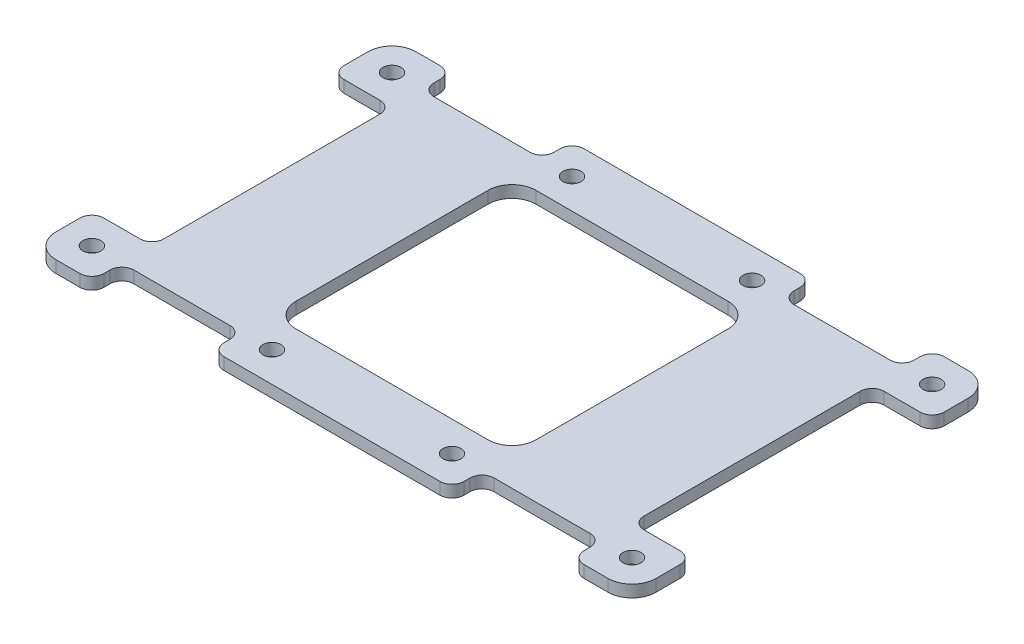
SolidWorks part; units mm, degrees
material "Thornel Mat VMA"
ref_plane "前视基准面" through (0, 0, 0) normal (0, 0, 1) x (1, 0, 0)
ref_plane "上视基准面" through (0, 0, 0) normal (0, 1, 0) x (1, 0, 0)
ref_plane "右视基准面" through (0, 0, 0) normal (1, 0, 0) x (0, 0, -1)
other "Configuration Table"
sketch "草图1" plane through (0, 0, 0) normal (0, 1, 0) x (1, 0, 0)
  line L1 (-50, -30) -> (50, -30)
  line L2 (-50, -30) -> (-50, 30)
  line L3 (-50, 30) -> (50, 30)
  line L4 (50, -30) -> (50, 30)
  line L5 (-50, -30) -> (50, 30) construction
  line L6 (-50, 30) -> (50, -30) construction
  point P0 (0, 0)
  dimension "D1" = 100
  dimension "D2" = 60
extrude "凸台-拉伸1" add sketch "草图1" along normal blind 2
sketch "草图3" plane through (0, 2, 0) normal (0, 1, 0) x (1, 0, 0)
  line L0 (-1000, 0) -> (49000, 0) construction
  line L1 (-42.4264, 42.4264) -> (0, 0) construction
  line L2 (-42.9749, 27.7358) -> (35312.3642, 35383.0749) construction
  line L3 (0, -1000) -> (0, 49000) construction
  circle A0 centre (0, 0) radius 60 construction
  circle A1 centre (-42.4264, 42.4264) radius 1.5
  circle A2 centre (-31.8198, 38.8909) radius 1.5
  circle A3 centre (-38.8909, 31.8198) radius 1.5
  circle A4 centre (-31.8198, -38.8909) radius 1.5
  circle A5 centre (-38.8909, -31.8198) radius 1.5
  circle A6 centre (-42.4264, -42.4264) radius 1.5
  circle A7 centre (31.8198, 38.8909) radius 1.5
  circle A8 centre (38.8909, 31.8198) radius 1.5
  circle A9 centre (42.4264, 42.4264) radius 1.5
  circle A10 centre (31.8198, -38.8909) radius 1.5
  circle A11 centre (42.4264, -42.4264) radius 1.5
  circle A12 centre (38.8909, -31.8198) radius 1.5
  dimension "D1" = 120
  dimension "D3" = 3
  dimension "D6" = 3
  dimension "D7" = 3
  dimension "D8" = 5
  dimension "D9" = 5
  dimension "D2" = 45
  dimension "D4" = 90
  dimension "D5" = 10
sketch "草图4" plane through (0, 2, 0) normal (0, 1, 0) x (1, 0, 0)
  line L1 (-20, -20) -> (20, -20)
  line L2 (-20, -20) -> (-20, 20)
  line L3 (-20, 20) -> (20, 20)
  line L4 (20, -20) -> (20, 20)
  line L5 (-20, -20) -> (20, 20) construction
  line L6 (-20, 20) -> (20, -20) construction
  point P0 (0, 0)
  dimension "D1" = 40
  dimension "D2" = 40
extrude "切除-拉伸3" cut sketch "草图4" against normal through all
sketch "草图5" plane through (0, 2, 0) normal (0, 1, 0) x (1, 0, 0)
  line L0 (-50, 30) -> (-50, -30) construction
  line L1 (-47, -20) -> (-45, -20)
  line L2 (-47, -20) -> (-47, 20)
  line L3 (-47, 20) -> (-45, 20)
  line L4 (-45, -20) -> (-45, 20)
  line L5 (-47, -20) -> (-45, 20) construction
  line L6 (-47, 20) -> (-45, -20) construction
  line L7 (0, -1000) -> (0, 49000) construction
  line L8 (47, -20) -> (45, -20)
  line L9 (47, 20) -> (45, 20)
  line L10 (45, -20) -> (45, 20)
  line L11 (47, -20) -> (47, 20)
  point P0 (-46, 0)
  dimension "D1" = 40
  dimension "D2" = 2
  dimension "D3" = 3
  dimension "D4" = 0
sketch "草图6" plane through (0, 2, 0) normal (0, 1, 0) x (1, 0, 0)
  line L0 (-1000, 0) -> (49000, 0) construction
  line L1 (0, -1000) -> (0, 49000) construction
  line L2 (-50, 30) -> (-50, -30) construction
  circle A0 centre (-45, 25) radius 1.5
  circle A1 centre (-45, -25) radius 1.5
  circle A2 centre (45, -25) radius 1.5
  circle A3 centre (45, 25) radius 1.5
  dimension "D1" = 3
  dimension "D2" = 25
  dimension "D3" = 5
extrude "切除-拉伸5" cut sketch "草图6" against normal through all
sketch "草图7" plane through (0, 2, 0) normal (0, 1, 0) x (1, 0, 0)
  line L0 (50, 30) -> (-50, 30) construction
  line L1 (-40, 30) -> (-20, 30)
  line L2 (-40, 30) -> (-40, 25)
  line L3 (-40, 25) -> (-20, 25)
  line L4 (-20, 30) -> (-20, 25)
  line L5 (-1000, 0) -> (49000, 0) construction
  line L6 (0, -1000) -> (0, 49000) construction
  line L7 (-50, 30) -> (-50, -30) construction
  line L8 (-40, -25) -> (-20, -25)
  line L9 (-20, -30) -> (-20, -25)
  line L10 (-40, -30) -> (-20, -30)
  line L11 (-40, -30) -> (-40, -25)
  line L12 (40, -30) -> (40, -25)
  line L13 (40, -30) -> (20, -30)
  line L14 (20, -30) -> (20, -25)
  line L15 (40, -25) -> (20, -25)
  line L16 (40, 25) -> (20, 25)
  line L17 (20, 30) -> (20, 25)
  line L18 (40, 30) -> (20, 30)
  line L19 (40, 30) -> (40, 25)
  point P10 (-40, 27.5)
  dimension "D1" = 20
  dimension "D2" = 5
  dimension "D3" = 10
extrude "切除-拉伸6" cut sketch "草图7" against normal through all
fillet "圆角1" radius 4 8 edges at (-50, 1, 30) (50, 1, 30) (50, 1, -30) (-50, 1, -30) (-20, 1, 20) (20, 1, 20) (20, 1, -20) (-20, 1, -20)
fillet "圆角2" radius 2 16 edges at (-40, 1, 25) (-40, 1, 30) (-20, 1, 30) (-20, 1, 25) (40, 1, 30) (40, 1, 25) (20, 1, 25) (20, 1, 30) (40, 1, -30) (40, 1, -25) (20, 1, -25) (20, 1, -30) (-20, 1, -30) (-20, 1, -25) (-40, 1, -25) (-40, 1, -30)
sketch "草图8" plane through (0, 2, 0) normal (0, 1, 0) x (1, 0, 0)
  line L0 (-20, 27) -> (-20, 28) construction
  line L1 (18, 30) -> (-18, 30) construction
  line L2 (-1000, 0) -> (49000, 0) construction
  line L3 (0, -1000) -> (0, 49000) construction
  circle A0 centre (-15, 25) radius 1.5
  circle A1 centre (-15, -25) radius 1.5
  circle A2 centre (15, -25) radius 1.5
  circle A3 centre (15, 25) radius 1.5
  dimension "D1" = 3
  dimension "D2" = 5
  dimension "D3" = 5
extrude "切除-拉伸7" cut sketch "草图8" against normal through all
sketch "草图9" plane through (0, 2, 0) normal (0, 1, 0) x (1, 0, 0)
  line L0 (-50, 26) -> (-50, -26) construction
  line L1 (-50, 20) -> (-40, 20)
  line L2 (-50, 20) -> (-50, -20)
  line L3 (-50, -20) -> (-40, -20)
  line L4 (-40, 20) -> (-40, -20)
  line L5 (0, -1000) -> (0, 49000) construction
  line L6 (50, -20) -> (40, -20)
  line L7 (40, 20) -> (40, -20)
  line L8 (50, 20) -> (40, 20)
  line L9 (50, 20) -> (50, -20)
  point P6 (-50, 0)
  dimension "D1" = 0
  dimension "D2" = 40
  dimension "D3" = 10
extrude "切除-拉伸9" cut sketch "草图9" against normal through all
fillet "圆角3" radius 2 8 edges at (50, 1, 20) (40, 1, 20) (40, 1, -20) (50, 1, -20) (-40, 1, 20) (-50, 1, 20) (-40, 1, -20) (-50, 1, -20)
